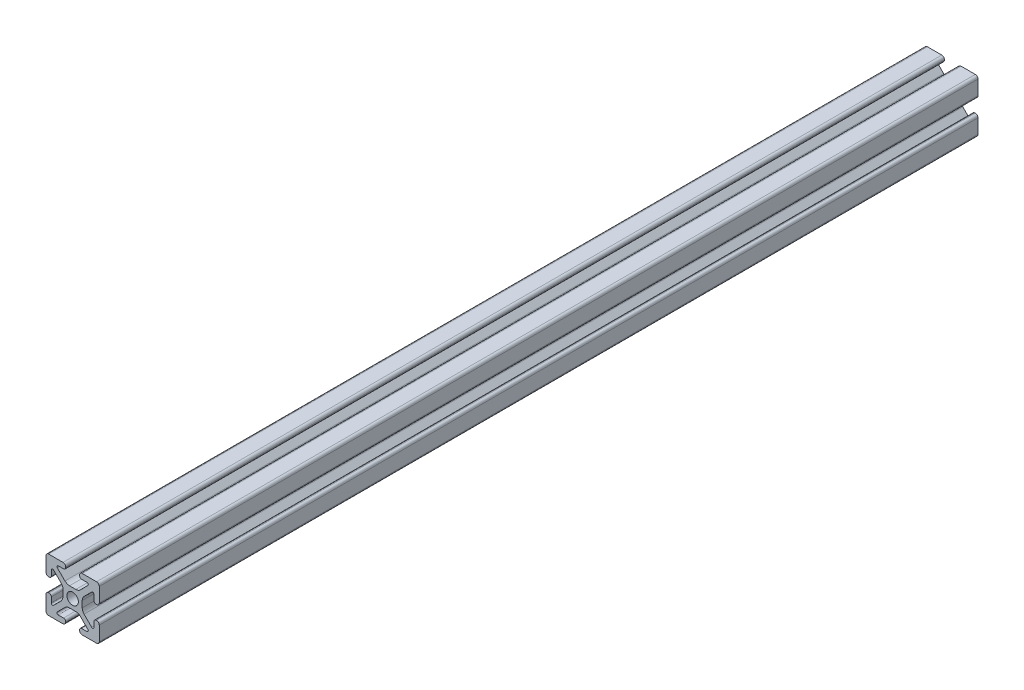
SolidWorks part; units mm, degrees
material "Aluminum 6061"
ref_plane "Front Plane" through (0, 0, 0) normal (0, 0, 1) x (1, 0, 0)
ref_plane "Top Plane" through (0, 0, 0) normal (0, 1, 0) x (1, 0, 0)
ref_plane "Right Plane" through (0, 0, 0) normal (1, 0, 0) x (0, 0, -1)
sketch "Esquisse1" plane through (0, 0, 0) normal (0, 0, 1) x (1, 0, 0)
  line B0 (-2.8857, 4.2999) -> (-5.7322, 7.1464)
  line B1 (-5.3787, 8) -> (-3.4, 8)
  line B2 (-2.6, 8.8) -> (-2.6, 9)
  line B3 (-3.6, 10) -> (-9, 10)
  line B4 (-10, 9) -> (-10, 3.6)
  line B5 (-9, 2.6) -> (-8.8, 2.6)
  line B6 (-8, 3.4) -> (-8, 5.3787)
  line B7 (-7.1464, 5.7322) -> (-4.2999, 2.8857)
  line B8 (-3.6, 1.196) -> (-3.6, -1.196)
  line B9 (-4.2999, -2.8857) -> (-7.1464, -5.7322)
  line B10 (-8, -5.3787) -> (-8, -3.4)
  line B11 (-8.8, -2.6) -> (-9, -2.6)
  line B12 (-10, -3.6) -> (-10, -9)
  line B13 (-9, -10) -> (-3.6, -10)
  line B14 (-2.6, -9) -> (-2.6, -8.8)
  line B15 (-3.4, -8) -> (-5.3787, -8)
  line B16 (-5.7322, -7.1464) -> (-2.8857, -4.2999)
  line B17 (-1.196, -3.6) -> (1.196, -3.6)
  line B18 (2.8857, -4.2999) -> (5.7322, -7.1464)
  line B19 (5.3787, -8) -> (3.4, -8)
  line B20 (2.6, -8.8) -> (2.6, -9)
  line B21 (3.6, -10) -> (9, -10)
  line B22 (10, -9) -> (10, -3.6)
  line B23 (9, -2.6) -> (8.8, -2.6)
  line B24 (8, -3.4) -> (8, -5.3787)
  line B25 (7.1464, -5.7322) -> (4.2999, -2.8857)
  line B26 (3.6, -1.196) -> (3.6, 1.196)
  line B27 (4.2999, 2.8857) -> (7.1464, 5.7322)
  line B28 (8, 5.3787) -> (8, 3.4)
  line B29 (8.8, 2.6) -> (9, 2.6)
  line B30 (10, 3.6) -> (10, 9)
  line B31 (9, 10) -> (3.6, 10)
  line B32 (2.6, 9) -> (2.6, 8.8)
  line B33 (3.4, 8) -> (5.3787, 8)
  line B34 (5.7322, 7.1464) -> (2.8857, 4.2999)
  line B35 (1.196, 3.6) -> (-1.196, 3.6)
  circle B36 centre (0, 0) radius 2.15
  arc B37 (-5.3787, 8) -> (-5.7322, 7.1464) centre (-5.3787, 7.5) ccw
  arc B38 (-2.6, 9) -> (-3.6, 10) centre (-3.6, 9) ccw
  arc B39 (-9, 10) -> (-10, 9) centre (-9, 9) ccw
  arc B40 (-10, 3.6) -> (-9, 2.6) centre (-9, 3.6) ccw
  arc B41 (-7.1464, 5.7322) -> (-8, 5.3787) centre (-7.5, 5.3787) ccw
  arc B42 (-3.6, 1.196) -> (-4.2999, 2.8857) centre (-5.9897, 1.196) ccw
  arc B43 (-4.2999, -2.8857) -> (-3.6, -1.196) centre (-7.4255, -0.6012) ccw
  arc B44 (-8, -5.3787) -> (-7.1464, -5.7322) centre (-7.5, -5.3787) ccw
  arc B45 (-9, -2.6) -> (-10, -3.6) centre (-9, -3.6) ccw
  arc B46 (-10, -9) -> (-9, -10) centre (-9, -9) ccw
  arc B47 (-3.6, -10) -> (-2.6, -9) centre (-3.851, -8.749) ccw
  arc B48 (-5.7322, -7.1464) -> (-5.3787, -8) centre (-5.3787, -7.5) ccw
  arc B49 (-1.196, -3.6) -> (-2.8857, -4.2999) centre (-1.196, -5.9897) ccw
  arc B50 (2.8857, -4.2999) -> (1.196, -3.6) centre (1.196, -5.9897) ccw
  arc B51 (5.3787, -8) -> (5.7322, -7.1464) centre (5.3787, -7.5) ccw
  arc B52 (2.6, -9) -> (3.6, -10) centre (3.6, -9) ccw
  arc B53 (9, -10) -> (10, -9) centre (9, -9) ccw
  arc B54 (10, -3.6) -> (9, -2.6) centre (9, -3.6) ccw
  arc B55 (7.1464, -5.7322) -> (8, -5.3787) centre (7.5, -5.3787) ccw
  arc B56 (3.6, -1.196) -> (4.2999, -2.8857) centre (5.9897, -1.196) ccw
  arc B57 (4.2999, 2.8857) -> (3.6, 1.196) centre (5.9897, 1.196) ccw
  arc B58 (8, 5.3787) -> (7.1464, 5.7322) centre (7.5, 5.3787) ccw
  arc B59 (9, 2.6) -> (10, 3.6) centre (9, 3.6) ccw
  arc B60 (10, 9) -> (9, 10) centre (9, 9) ccw
  arc B61 (3.6, 10) -> (2.6, 9) centre (3.6, 9) ccw
  arc B62 (5.7322, 7.1464) -> (5.3787, 8) centre (5.3787, 7.5) ccw
  arc B63 (1.196, 3.6) -> (2.8857, 4.2999) centre (1.196, 5.9897) ccw
  arc B64 (-2.8857, 4.2999) -> (-1.196, 3.6) centre (-0.8105, 6.9201) ccw
  line B65 (0, 0) -> (-2.8465, 2.8465) construction
  line B66 (0, 0) -> (-15.589, 0) construction
  line B67 (0, 0) -> (0, 15.589) construction
  line B68 (0, 0) -> (2.8465, 2.8465) construction
  arc B69 (-3.4, 8) -> (-2.6, 8.8) centre (-3.4, 8.8) ccw
  arc B70 (-8.8, 2.6) -> (-8, 3.4) centre (-8.8, 3.4) ccw
  arc B71 (-8, -3.4) -> (-8.8, -2.6) centre (-8.8, -3.4) ccw
  arc B72 (-3.4, -8) -> (-2.6, -8.8) centre (-3.4, -8.8) cw
  arc B73 (2.6, -8.8) -> (3.4, -8) centre (3.4, -8.8) cw
  arc B74 (8, -3.4) -> (8.8, -2.6) centre (8.8, -3.4) cw
  arc B75 (8.8, 2.6) -> (8, 3.4) centre (8.8, 3.4) cw
  arc B76 (3.4, 8) -> (2.6, 8.8) centre (3.4, 8.8) cw
sketch_block_instance "Bloc2-1"
sketch_block "Bloc2" parameters "D1"=6.1, "D2"=0.2, "D8"=0.8, "D9"=0.9436, "D3"=4.2243, "D4"=4.3539, "D5"=1.7395, "D6"=7.1083, "D7"=1.7395
extrude "Boss.-Extru.1" add sketch "Esquisse1" along normal blind 330
sketch "Esquisse3" [suppressed] plane through (0, 10, 0) normal (0, 1, 0) x (1, 0, 0)
  line L0 (9.6, 0) -> (5.15, 0) construction
  line L1 (9.6, -300) -> (5.15, -300) construction
  circle A0 centre (0, -290) radius 2.5
  circle A1 centre (0, -10) radius 2.5
  dimension "D2" = 5
  dimension "D3" = 10
  dimension "D1" = 10
extrude "Enlèv. mat.-Extru.1" [suppressed] cut sketch "Esquisse3" against normal through all
sketch "Esquisse4" [suppressed] plane through (0, 10, 0) normal (0, 1, 0) x (1, 0, 0)
  circle A0 centre (0, -10) radius 7
  circle A1 centre (0, -290) radius 7
  arc A2 (-1.3704, -287.909) -> (-1.3704, -292.091) centre (0, -290) ccw construction
  arc A3 (-1.3704, -7.909) -> (-1.3704, -12.091) centre (0, -10) ccw construction
  dimension "D1" = 14
extrude "Enlèv. mat.-Extru.2" [suppressed] cut sketch "Esquisse4" against normal blind 6
sketch "Esquisse5" plane through (10, 0, 0) normal (1, 0, 0) x (0, 0, -1)
  line L0 (-330, 9) -> (-330, -9) construction
  line L1 (-330, 0) -> (-177.1435, 0) construction
  circle A0 centre (-280, 0) radius 4.05
  dimension "D1" = 8.1
  dimension "D2" = 50
extrude "Enlèv. mat.-Extru.6" [suppressed] cut sketch "Esquisse5" against normal through all
sketch "Esquisse6" [suppressed] plane through (10, 0, 0) normal (1, 0, 0) x (0, 0, -1)
  line L0 (-450, 9) -> (0, -9) construction
  circle A0 centre (-225, 0) radius 3
  dimension "D1" = 6
extrude "Enlèv. mat.-Extru.7" [suppressed] cut sketch "Esquisse6" against normal through all
sketch "Esquisse7" [suppressed] plane through (0, 10, 0) normal (0, 1, 0) x (1, 0, 0)
  line L0 (-9, -450) -> (9, 0) construction
  circle A0 centre (0, -225) radius 3
  dimension "D1" = 6
extrude "Enlèv. mat.-Extru.8" [suppressed] cut sketch "Esquisse7" against normal through all
equation "\"Length\"= 500"
